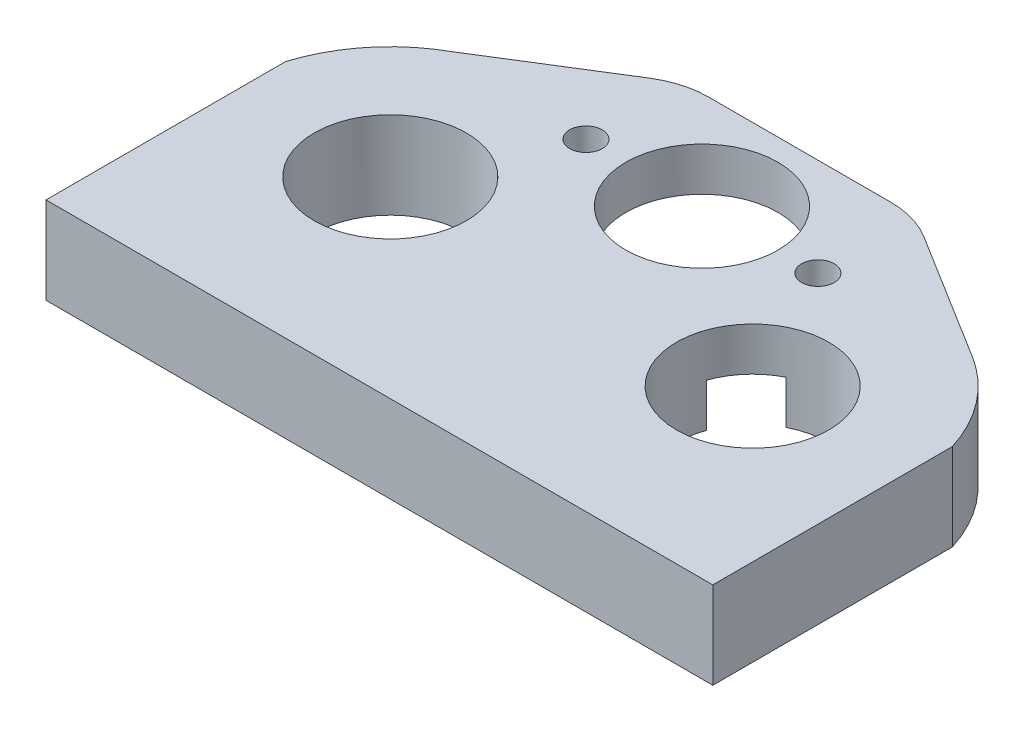
SolidWorks part; units mm, degrees
material "Beech"
ref_plane "Front Plane" through (0, 0, 0) normal (0, 0, 1) x (1, 0, 0)
ref_plane "Top Plane" through (0, 0, 0) normal (0, 1, 0) x (1, 0, 0)
ref_plane "Right Plane" through (0, 0, 0) normal (1, 0, 0) x (0, 0, -1)
sketch "Sketch1" plane through (0, 0, 0) normal (0, 1, 0) x (1, 0, 0)
  line L1 (-46, 28) -> (46, 28)
  line L2 (-46, 28) -> (-46, -28)
  line L3 (-46, -28) -> (46, -28)
  line L4 (46, 28) -> (46, -28)
  line L5 (-46, 28) -> (46, -28) construction
  line L6 (-46, -28) -> (46, 28) construction
  point P0 (0, 0)
  dimension "D1" = 56
  dimension "D2" = 92
extrude "Boss-Extrude1" add sketch "Sketch1" along normal blind 12
sketch "Sketch8" plane through (0, 12, 0) normal (0, 1, 0) x (1, 0, 0)
  line L1 (-46, 28) -> (46, 28)
  line L2 (-46, 28) -> (-46, 30)
  line L3 (-46, 30) -> (46, 30)
  line L4 (46, 28) -> (46, 30)
  dimension "D1" = 2
extrude "Boss-Extrude3" add sketch "Sketch8" against normal blind 12
sketch "Sketch2" plane through (0, 12, 0) normal (0, 1, 0) x (1, 0, 0)
  line L0 (-55.7629, -1.5) -> (57.1831, -1.5) construction
  line L1 (-46, -28) -> (46, -28) construction
  circle A0 centre (-25, -1.5) radius 10.5
  circle A1 centre (25, -1.5) radius 10.5
  point P6 (0, -28)
  dimension "D1" = 21
  dimension "D2" = 21
  dimension "D3" = 50
  dimension "D4" = 25
  dimension "D5" = 26.5
extrude "Cut-Extrude1" cut sketch "Sketch2" against normal up to next
sketch "Sketch10" plane through (0, 12, 0) normal (0, 1, 0) x (1, 0, 0)
  line L0 (-46, 5.0574) -> (-46, 30)
  line L1 (46, 30) -> (-46, 30) construction
  line L2 (-46, 30) -> (-16, 30)
  line L4 (-16, 30) -> (-35.6673, 17.7408)
  line L5 (46, 5.0574) -> (46, 30)
  line L6 (46, 30) -> (16, 30)
  line L8 (16, 30) -> (36.6154, 17.1838)
  arc A2 (-46, 5.0574) -> (-35.6673, 17.7408) centre (-25, -1.5) cw
  arc A3 (46, 5.0574) -> (36.6154, 17.1838) centre (25, -1.5) ccw
  dimension "D1" = 30
  dimension "D2" = 30
extrude "Cut-Extrude5" cut sketch "Sketch10" against normal up to next
fillet "Fillet2" radius 12 2 edges at (16, 6, -30) (-16, 6, -30)
sketch "Sketch11" plane through (0, 0, 0) normal (0, -1, 0) x (1, 0, 0)
  line L2 (22, -16.5) -> (22, -26.2699)
  line L3 (36.6154, -17.1838) -> (18.9096, -28.1911) construction
  line L4 (-16.5454, -2) -> (16.5454, -2)
  line L5 (16.5454, -31) -> (-16.5454, -31)
  line L6 (22, -26.2699) -> (16.5454, -31)
  line L7 (-22, -16.5) -> (-22, -26.26)
  line L8 (-18.914, -28.1836) -> (-35.6673, -17.7408) construction
  line L9 (-22, -26.26) -> (-16.5454, -31)
  arc A4 (22, -16.5) -> (16.5454, -2) centre (0, -16.5) ccw
  arc A5 (-16.5454, -2) -> (-22, -16.5) centre (0, -16.5) ccw
extrude "Cut-Extrude6" cut sketch "Sketch11" against normal blind 6
sketch "Sketch12" plane through (0, 0, 0) normal (0, -1, 0) x (1, 0, 0)
  circle A0 centre (16, -16.5) radius 2.25 construction
  circle A1 centre (-16, -16.5) radius 2.25 construction
  circle A2 centre (0, -16.5) radius 10.5 construction
  circle A3 centre (16, -16.5) radius 2.25
  circle A4 centre (-16, -16.5) radius 2.25
  circle A5 centre (0, -16.5) radius 10.5
extrude "Cut-Extrude7" cut sketch "Sketch12" against normal up to next
